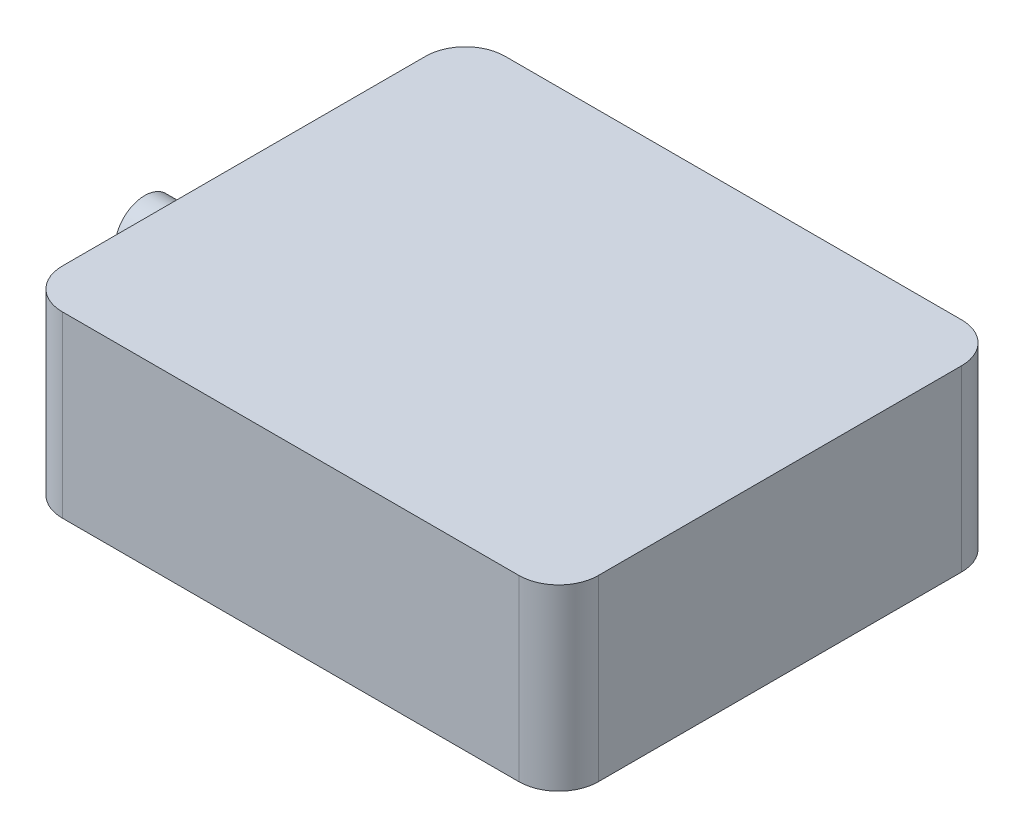
SolidWorks part; units mm, degrees
ref_plane "Front Plane" through (0, 0, 0) normal (0, 0, 1) x (1, 0, 0)
ref_plane "Top Plane" through (0, 0, 0) normal (0, 1, 0) x (1, 0, 0)
ref_plane "Right Plane" through (0, 0, 0) normal (1, 0, 0) x (0, 0, -1)
sketch "Sketch1" plane through (0, 0, 0) normal (0, 1, 0) x (1, 0, 0)
  line L1 (-13.5, -11.15) -> (13.5, -11.15)
  line L2 (-13.5, -11.15) -> (-13.5, 11.15)
  line L3 (-13.5, 11.15) -> (13.5, 11.15)
  line L4 (13.5, -11.15) -> (13.5, 11.15)
  line L5 (0, 11.15) -> (0, -11.15) construction
  line L6 (-13.5, 0) -> (13.5, 0) construction
  point P0 (0, 0)
  dimension "D1" = 27
  dimension "D2" = 22.3
extrude "Boss-Extrude1" add sketch "Sketch1" along normal blind 9
sketch "Sketch2" plane through (-13.5, 0, 0) normal (-1, 0, 0) x (0, 0, 1)
  line L0 (0, 9) -> (0, 0) construction
  line L1 (-11.15, 9) -> (11.15, 9) construction
  circle A0 centre (0, 3.5) radius 1.5
  point P7 (0, 2)
  dimension "D1" = 3
  dimension "D2" = 2
extrude "Boss-Extrude3" add sketch "Sketch2" along normal blind 5
fillet "Fillet1" radius 2 4 edges at (13.5, 4.5, -11.15) (13.5, 4.5, 11.15) (-13.5, 4.5, 11.15) (-13.5, 4.5, -11.15)
